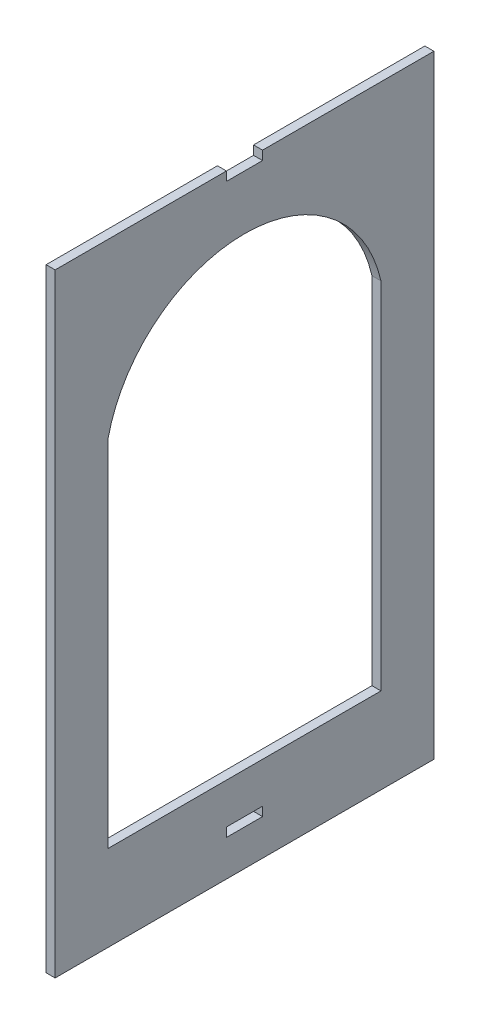
SolidWorks part; units mm, degrees
ref_plane "Front" through (0, 0, 0) normal (0, 0, 1) x (1, 0, 0)
ref_plane "Top" through (0, 0, 0) normal (0, 1, 0) x (1, 0, 0)
ref_plane "Right" through (0, 0, 0) normal (1, 0, 0) x (0, 0, -1)
sketch "Sketch1" plane through (0, 0, 0) normal (1, 0, 0) x (0, 0, -1)
  line L0 (12.7, 215.9) -> (133.35, 215.9)
  line L1 (-133.35, 215.9) -> (-12.7, 215.9)
  line L2 (-133.35, 215.9) -> (-133.35, -215.9)
  line L3 (-133.35, -215.9) -> (133.35, -215.9)
  line L4 (133.35, 215.9) -> (133.35, -215.9)
  line L5 (-133.35, 215.9) -> (133.35, -215.9) construction
  line L6 (-133.35, -215.9) -> (133.35, 215.9) construction
  line L7 (-12.7, 209.55) -> (12.7, 209.55)
  line L8 (-12.7, 209.55) -> (-12.7, 215.9)
  line L10 (12.7, 209.55) -> (12.7, 215.9)
  line L11 (-12.7, 209.55) -> (0, 203.2) construction
  line L12 (0, 203.2) -> (12.7, 209.55) construction
  line L14 (-12.7, -184.15) -> (12.7, -184.15)
  line L15 (-12.7, -184.15) -> (-12.7, -190.5)
  line L16 (-12.7, -190.5) -> (12.7, -190.5)
  line L17 (12.7, -184.15) -> (12.7, -190.5)
  line L18 (-12.7, -184.15) -> (12.7, -190.5) construction
  line L19 (-12.7, -190.5) -> (12.7, -184.15) construction
  line L21 (-96.07, 94.4581) -> (-96.07, -155.5419)
  line L22 (-96.07, -155.5419) -> (96.07, -155.5419)
  line L23 (96.07, 94.4581) -> (96.07, -155.5419)
  line L24 (-84.6249, 137.0118) -> (96.07, -155.5419) construction
  arc A0 (-96.07, 94.4581) -> (96.07, 94.4581) centre (0, 72.8095) cw
  point P0 (0, 0)
  point P6 (0, 203.2)
  point P7 (0, -187.325)
  point P17 (0, 0)
  dimension "D1" = 6.35
  dimension "D2" = 25.4
  dimension "D3" = 266.7
  dimension "D4" = 120.65
  dimension "D5" = 431.8
  dimension "D6" = 6.35
  dimension "D7" = 25.4
  dimension "D8" = 120.65
  dimension "D9" = 250
  dimension "D10" = 250
  dimension "D11" = 37.28
  dimension "D12" = 37.28
extrude "Boss-Extrude1" add sketch "Sketch1" along normal blind 6.35
